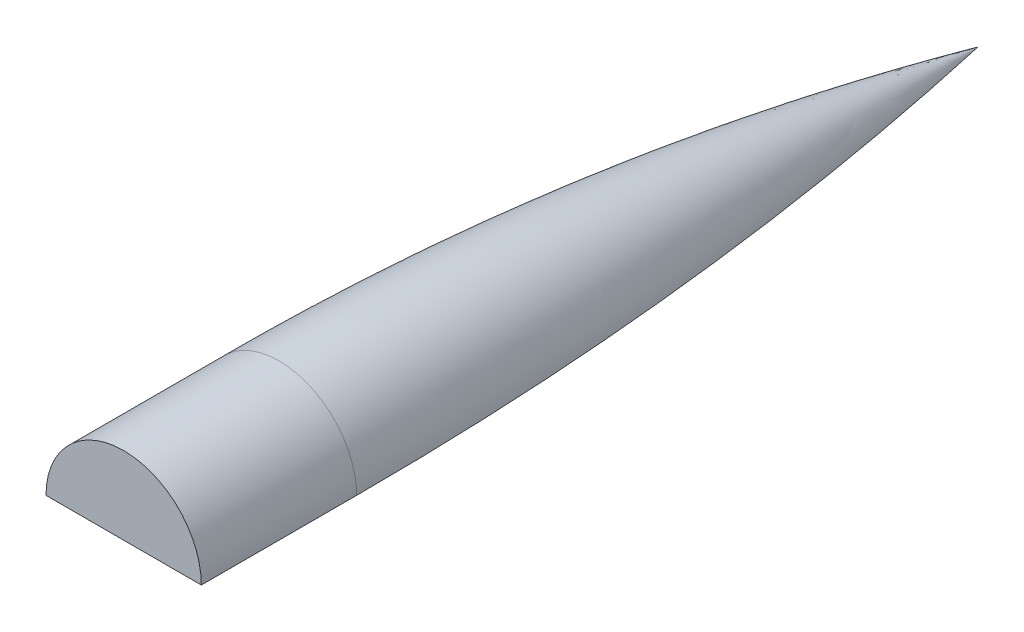
SolidWorks part; units mm, degrees
ref_plane "Front Plane" through (0, 0, 0) normal (0, 0, 1) x (1, 0, 0)
ref_plane "Top Plane" through (0, 0, 0) normal (0, 1, 0) x (1, 0, 0)
ref_plane "Right Plane" through (0, 0, 0) normal (1, 0, 0) x (0, 0, -1)
sketch "Sketch1" plane through (0, 0, 0) normal (0, 1, 0) x (1, 0, 0)
  line L0 (0, 0) -> (0, 339.1186) construction
  line L1 (0, 339.1186) -> (0, -577.5049) construction
  line L2 (0, -577.5049) -> (0, 0) construction
  line L3 (0, 0) -> (-228.8127, 0) construction
  line L4 (-228.8127, 0) -> (380.1501, 0) construction
  line L5 (0, 685.8) -> (0, 0)
  line L6 (0, 0) -> (-76.2, 0)
  line L7 (-76.2, 0) -> (-76.2, 263.1035) construction
  line L8 (-76.2, 0) -> (-76.2, -152.4)
  line L9 (-76.2, -152.4) -> (0, -152.4)
  line L10 (0, 0) -> (0, -152.4)
  arc A0 (0, 685.8) -> (-76.2, 0) centre (3048, 0) ccw
  dimension "D1" = 685.8
  dimension "D2" = 76.2
  dimension "D3" = 152.4
revolve "Revolve1" add sketch "Sketch1" angle 180 about L0
